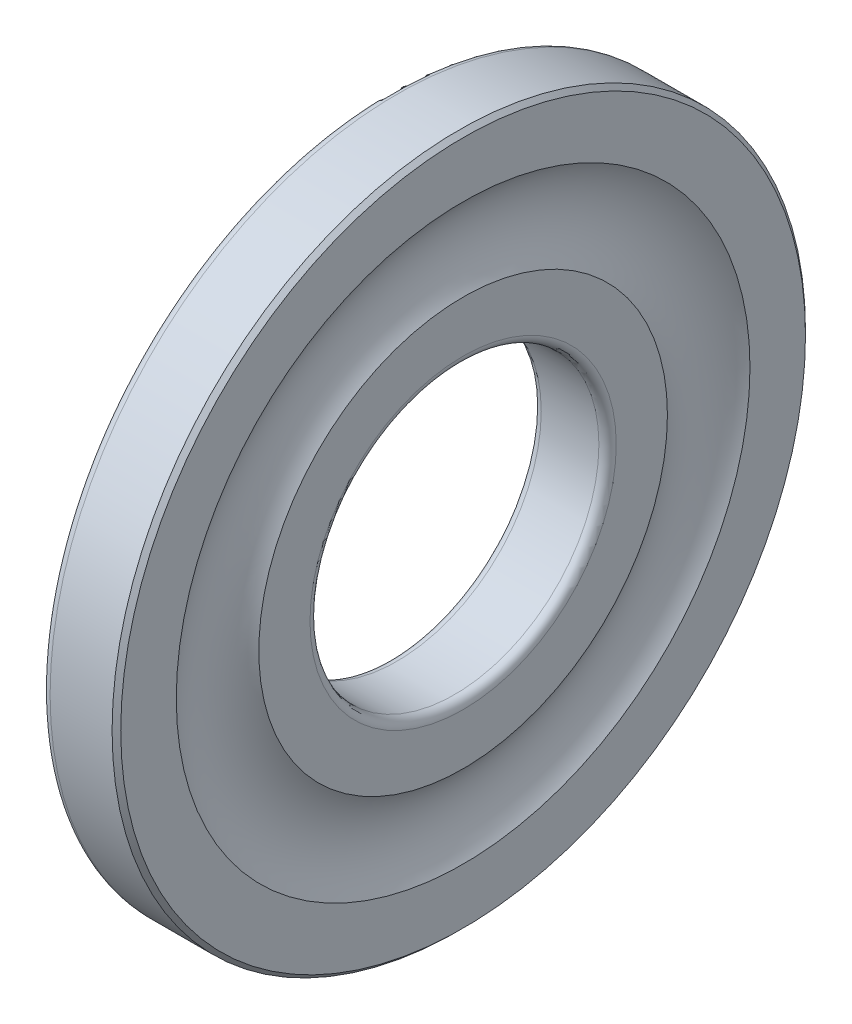
SolidWorks part; units mm, degrees
ref_plane "Спереди" through (0, 0, 0) normal (0, 0, 1) x (1, 0, 0)
ref_plane "Сверху" through (0, 0, 0) normal (0, 1, 0) x (1, 0, 0)
ref_plane "Справа" through (0, 0, 0) normal (1, 0, 0) x (0, 0, -1)
sketch "Эскиз1" plane through (0, 0, 0) normal (0, 0, 1) x (1, 0, 0)
  line L0 (2.5952, 5.3) -> (2.5952, 7.0714)
  line L1 (2.5952, 9.9286) -> (2.5952, 12)
  line L2 (2.5952, 12) -> (0.3, 12)
  line L3 (0, 11.7) -> (0, 5.3)
  line L4 (0.3, 5) -> (2.2952, 5)
  line L5 (-0.0013, 0) -> (2.5965, 0) construction
  arc A0 (2.5952, 7.0714) -> (2.5952, 9.9286) centre (4.5, 8.5) cw
  arc A1 (0.3, 12) -> (0, 11.7) centre (0.3, 11.7) ccw
  arc A2 (0, 5.3) -> (0.3, 5) centre (0.3, 5.3) ccw
  arc A3 (2.2952, 5) -> (2.5952, 5.3) centre (2.2952, 5.3) ccw
revolve "Повернуть1" add sketch "Эскиз1" angle 360 about L5
chamfer "Фаска1" distance 0.15 angle 45 1 edges at (2.5952, 0, -12)
sketch "Эскиз2" plane through (0, 0, 0) normal (-1, 0, 0) x (0, 0, 1)
  line L0 (-3.4154, 9.223) -> (3.4154, 9.223) construction
  line L1 (8.5, -4.9075) -> (8.5, 4.9075) construction
  line L2 (8.5, 4.9075) -> (0, 9.815) construction
  line L3 (0, 9.815) -> (-8.5, 4.9075) construction
  line L4 (-8.5, 4.9075) -> (-8.5, -4.9075) construction
  line L5 (-8.5, -4.9075) -> (0, -9.815) construction
  line L6 (0, -9.815) -> (8.5, -4.9075) construction
  circle A0 centre (0, 0) radius 8.5 construction
  arc A1 (-3.4154, 9.223) -> (3.4154, 9.223) centre (0, 0) cw construction
  circle A2 centre (0, 0) radius 11.7 construction
  text T0 "51100" font "Arial" height 1.8
  point P15 (-4.6025, 8.7566)
  point P16 (-3.4154, 9.223)
  dimension "D1" = 17
extrude "Вырез-Вытянуть1" cut sketch "Эскиз2" against normal blind 0.01
